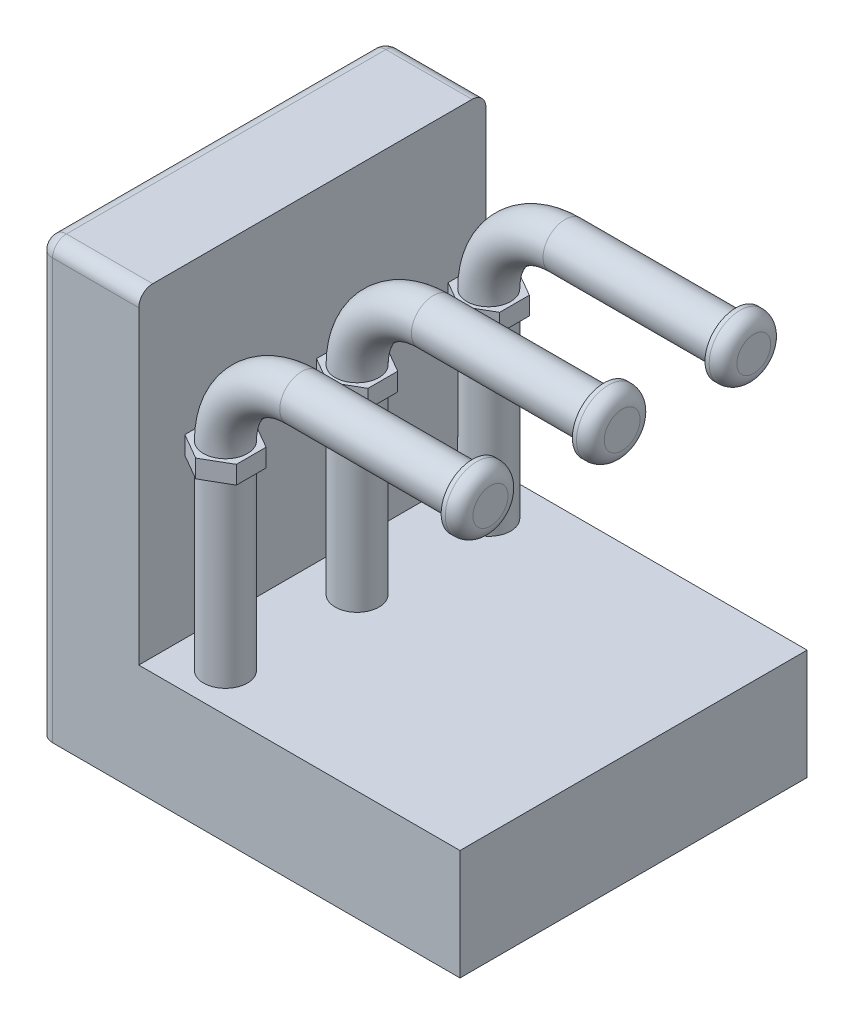
SolidWorks part; units mm, degrees
ref_plane "Alzado" through (0, 0, 0) normal (0, 0, 1) x (1, 0, 0)
ref_plane "Planta" through (0, 0, 0) normal (0, 1, 0) x (1, 0, 0)
ref_plane "Vista lateral" through (0, 0, 0) normal (1, 0, 0) x (0, 0, -1)
sketch "Croquis1" plane through (0, 0, 0) normal (0, 1, 0) x (1, 0, 0)
  line L1 (-304, 250.5) -> (304, 250.5)
  line L2 (-304, 250.5) -> (-304, -250.5)
  line L3 (-304, -250.5) -> (304, -250.5)
  line L4 (304, 250.5) -> (304, -250.5)
  line L5 (-304, 250.5) -> (304, -250.5) construction
  line L6 (-304, -250.5) -> (304, 250.5) construction
  point P0 (0, 0)
  dimension "D1" = 608
  dimension "D2" = 501
extrude "Saliente-Extruir1" add sketch "Croquis1" along normal blind 626
sketch "Croquis2" plane through (0, 0, 250.5) normal (0, 0, 1) x (1, 0, 0)
  line L0 (-159.5692, 626) -> (-159.5692, 159.3652)
  line L1 (-304, 626) -> (304, 626) construction
  line L2 (-159.5692, 159.3652) -> (304, 159.3652)
  line L3 (304, 626) -> (304, 0) construction
  line L4 (304, 159.3652) -> (304, 626)
  line L5 (304, 626) -> (-159.5692, 626)
extrude "Cortar-Extruir1" cut sketch "Croquis2" against normal blind 626
sketch "Croquis3" plane through (0, 159.3652, 0) normal (0, 1, 0) x (1, 0, 0)
  circle A0 centre (-90.2988, -194.6868) radius 31.6861
sketch3d "Croquis3D1"
  line L0 (-90.2988, 159.3652, 194.6868) -> (-90.2988, 446.2845, 194.6868)
  line L1 (19.7012, 556.2845, 194.6868) -> (266.216, 556.2845, 194.6868)
  arc A0 (-90.2988, 446.2845, 194.6868) -> (19.7012, 556.2845, 194.6868) centre (19.7012, 446.2845, 194.6868) ccw
  point P6 (-90.2988, 556.2845, 194.6868)
  point P7 (19.7012, 446.2845, 84.6868)
  dimension "D1" = 110
sweep "Barrer1" add profiles "Croquis3" path "Croquis3D1"
ref_plane "Plano1" through (0, 446.2845, 0) normal (0, -1, 0) x (-1, 0, 0)
sketch "Croquis4" plane through (0, 446.2845, 0) normal (0, -1, 0) x (-1, 0, 0)
  line L1 (90.2988, -151.7809) -> (53.1412, -173.2338)
  line L2 (53.1412, -173.2338) -> (53.1412, -216.1398)
  line L3 (53.1412, -216.1398) -> (90.2988, -237.5928)
  line L4 (90.2988, -237.5928) -> (127.4565, -216.1398)
  line L5 (127.4565, -216.1398) -> (127.4565, -173.2338)
  line L6 (127.4565, -173.2338) -> (90.2988, -151.7809)
  circle A0 centre (90.2988, -194.6868) radius 37.1577 construction
extrude "Saliente-Extruir2" add sketch "Croquis4" along normal blind 26
pattern_linear "MatrizL1" count 3 spacing 190 along (0, 0, -1) of "Saliente-Extruir2", "Barrer1"
sketch "Croquis5" plane through (266.216, 0, 0) normal (1, 0, 0) x (0, 0, -1)
  circle A0 centre (-194.6868, 556.2845) radius 45.2796
extrude "Saliente-Extruir3" add sketch "Croquis5" along normal blind 26
fillet "Redondeo1" radius 20 1 edges at (292.216, 556.2845, 149.4072)
sketch "Croquis6" plane through (266.216, 0, 0) normal (1, 0, 0) x (0, 0, -1)
  circle A0 centre (-4.6868, 556.2845) radius 45.847
  circle A1 centre (185.3132, 556.2845) radius 44.4456
extrude "Saliente-Extruir4" add sketch "Croquis6" along normal blind 26
fillet "Redondeo2" radius 20 2 edges at (292.216, 556.2845, -41.1602) (292.216, 556.2845, -229.7588)
fillet "Redondeo3" radius 20 2 edges at (-231.7846, 626, -250.5) (-231.7846, 626, 250.5)
fillet "Redondeo4" radius 20 5 edges at (-304, 620.1421, -244.6421) (-304, 626, 0) (-304, 620.1421, 244.6421) (-304, 303, -250.5) (-304, 303, 250.5)
sketch "Croquis7" plane through (-304, 0, 0) normal (-1, 0, 0) x (0, 0, 1)
  line L1 (-110.5434, 499.6034) -> (110.5434, 499.6034)
  line L2 (-110.5434, 499.6034) -> (-110.5434, 244.2493)
  line L3 (-110.5434, 244.2493) -> (110.5434, 244.2493)
  line L4 (110.5434, 499.6034) -> (110.5434, 244.2493)
  line L5 (-110.5434, 499.6034) -> (110.5434, 244.2493) construction
  line L6 (-110.5434, 244.2493) -> (110.5434, 499.6034) construction
  point P0 (0, 371.9264)
extrude "Cortar-Extruir2" cut sketch "Croquis7" against normal blind 0.01
sketch "Croquis8" plane through (-304, 0, 0) normal (-1, 0, 0) x (0, 0, 1)
  line L1 (-206.1322, 219.8441) -> (-171.7768, 219.8441)
  line L2 (-206.1322, 219.8441) -> (-206.1322, 185.4887)
  line L3 (-206.1322, 185.4887) -> (-171.7768, 185.4887)
  line L4 (-171.7768, 219.8441) -> (-171.7768, 185.4887)
  line L5 (-206.1322, 219.8441) -> (-171.7768, 185.4887) construction
  line L6 (-206.1322, 185.4887) -> (-171.7768, 219.8441) construction
  point P0 (-188.9545, 202.6664)
extrude "Cortar-Extruir3" cut sketch "Croquis8" against normal blind 20
pattern_linear "MatrizL2" count 7 spacing 60 along (0, 0, 1) of "Cortar-Extruir3"
pattern_linear "MatrizL3" count 4 spacing 40 along (0, -1, 0) of "MatrizL2", "Cortar-Extruir3"
